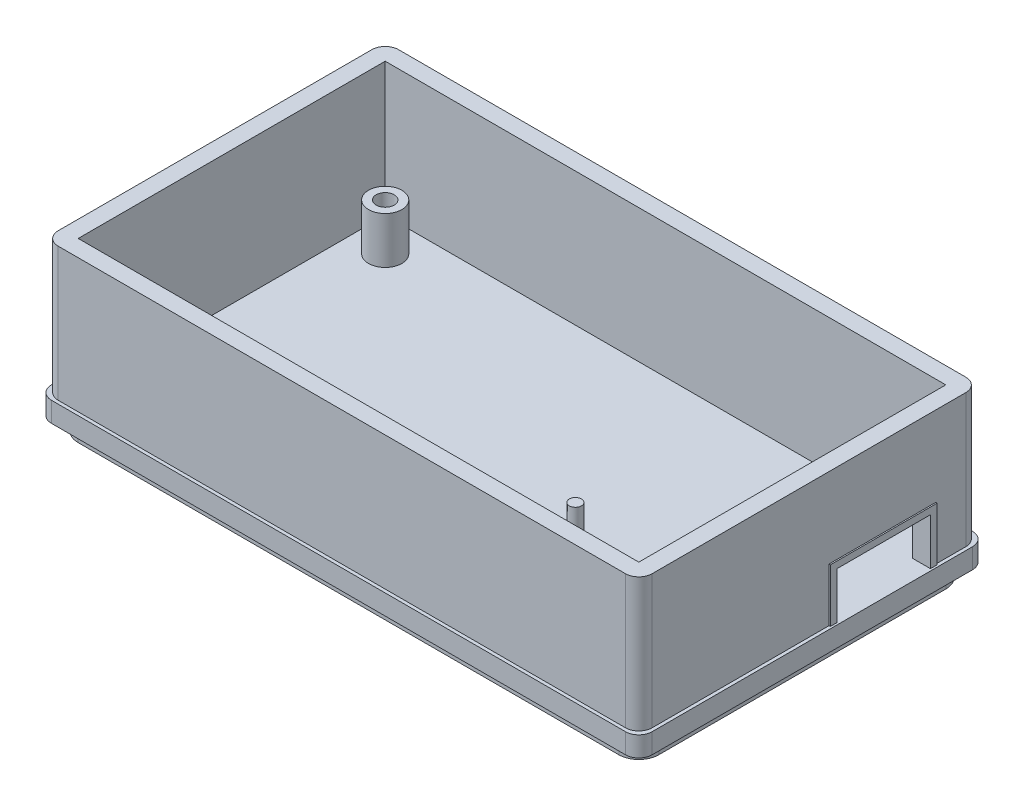
SolidWorks part; units mm, degrees
ref_plane "Front Plane" through (0, 0, 0) normal (0, 0, 1) x (1, 0, 0)
ref_plane "Top Plane" through (0, 0, 0) normal (0, 1, 0) x (1, 0, 0)
ref_plane "Right Plane" through (0, 0, 0) normal (1, 0, 0) x (0, 0, -1)
sketch "Sketch1" plane through (0, 0, 0) normal (0, 1, 0) x (1, 0, 0)
  line L1 (-45, 26) -> (45, 26)
  line L2 (-45, 26) -> (-45, -26)
  line L3 (-45, -26) -> (45, -26)
  line L4 (45, 26) -> (45, -26)
  dimension "D1" = 52
  dimension "D2" = 90
  dimension "D3" = 45
  dimension "D4" = 26
extrude "Boss-Extrude1" add sketch "Sketch1" along normal blind 3
sketch "Sketch3" plane through (0, 0, 0) normal (0, 1, 0) x (1, 0, 0)
  line L1 (-41.5, 22.5) -> (41.5, 22.5)
  line L2 (-41.5, 22.5) -> (-41.5, -22.5)
  line L3 (-41.5, -22.5) -> (41.5, -22.5)
  line L4 (41.5, 22.5) -> (41.5, -22.5)
  dimension "D1" = 45
  dimension "D2" = 83
  dimension "D3" = 41.5
  dimension "D4" = 22.5
sketch "Sketch4" plane through (0, 0, 0) normal (0, 1, 0) x (1, 0, 0)
  line L2 (-41.5, -22.5) -> (41.5, -22.5) construction
  line L3 (-41.5, 22.5) -> (-41.5, -22.5) construction
  circle A1 centre (29, -19.5) radius 2.5
  circle A2 centre (-37, 18) radius 2.5
  circle A3 centre (-37, -16.5) radius 2.5
  dimension "D4" = 5
  dimension "D5" = 3
  dimension "D8" = 4.5
  dimension "D9" = 6
extrude "Boss-Extrude2" add sketch "Sketch4" along normal blind 7 from surface at 3 starting at face at (0, 3, 0)
sketch "Sketch5" plane through (0, 0, 0) normal (0, 1, 0) x (1, 0, 0)
  circle A0 centre (-37, 18) radius 1.35
  circle A1 centre (-37, -16.5) radius 1.35
extrude "Cut-Extrude2" cut sketch "Sketch5" against normal through all both and the other way through all from surface at 10 starting at face at (-37, 10, -15.5)
sketch "Sketch6" plane through (0, 0, 0) normal (0, 1, 0) x (1, 0, 0)
  circle A0 centre (29, -19.5) radius 0.9
  dimension "D1" = 1.8
extrude "Boss-Extrude3" add sketch "Sketch6" along normal blind 12.5 from surface at 10 starting at face at (29, 10, 22)
sketch "Sketch7" plane through (0, 0, 0) normal (0, 1, 0) x (1, 0, 0)
  line L4 (40.5, 21.5) -> (-40.5, 21.5)
  line L5 (-40.5, 21.5) -> (-40.5, -21.5)
  line L6 (-40.5, -21.5) -> (40.5, -21.5)
  line L7 (40.5, -21.5) -> (40.5, 21.5)
  line L8 (43.5, 24.5) -> (-43.5, 24.5)
  line L9 (43.5, -24.5) -> (43.5, 24.5)
  line L10 (-43.5, -24.5) -> (43.5, -24.5)
  line L11 (-43.5, 24.5) -> (-43.5, -24.5)
  line L12 (43.5, 24.5) -> (-43.5, 24.5)
  line L13 (43.5, -24.5) -> (43.5, 24.5)
  line L14 (-43.5, -24.5) -> (43.5, -24.5)
  line L15 (-43.5, 24.5) -> (-43.5, -24.5)
  dimension "D1" = 2
  dimension "D2" = 3
extrude "Boss-Extrude4" add sketch "Sketch7" against normal blind 2
fillet "Fillet1" radius 3 4 edges at (-43.5, -1, 24.5) (-43.5, -1, -24.5) (43.5, -1, 24.5) (43.5, -1, -24.5)
sketch "Sketch8" plane through (0, 0, 0) normal (0, 1, 0) x (1, 0, 0)
  line L4 (44.5, 25.5) -> (-44.5, 25.5)
  line L5 (-44.5, 25.5) -> (-44.5, -25.5)
  line L6 (-44.5, -25.5) -> (44.5, -25.5)
  line L7 (44.5, -25.5) -> (44.5, 25.5)
  line L8 (42, 23) -> (-42, 23)
  line L9 (42, -23) -> (42, 23)
  line L10 (-42, -23) -> (42, -23)
  line L11 (-42, 23) -> (-42, -23)
  line L12 (42, 23) -> (-42, 23)
  line L13 (42, -23) -> (42, 23)
  line L14 (-42, -23) -> (42, -23)
  line L15 (-42, 23) -> (-42, -23)
  dimension "D1" = 0.5
  dimension "D2" = 2.5
extrude "Boss-Extrude8" add sketch "Sketch8" along normal blind 20 from surface at 3 starting at face at (29, 3, 22)
fillet "Fillet2" radius 2 8 edges at (-45, 1.5, 26) (-44.5, 13, 25.5) (-45, 1.5, -26) (-44.5, 13, -25.5) (45, 1.5, -26) (45, 1.5, 26) (44.5, 13, -25.5) (44.5, 13, 25.5)
sketch "Sketch9" plane through (0, 0, 0) normal (1, 0, 0) x (0, 0, -1)
  line L1 (4, 10) -> (18, 10)
  line L2 (4, 10) -> (4, 3)
  line L3 (4, 3) -> (18, 3)
  line L4 (18, 10) -> (18, 3)
  dimension "D1" = 14
  dimension "D2" = 7
  dimension "D4" = 5.5
extrude "Cut-Extrude3" cut sketch "Sketch9" along normal blind 15 from surface at 42 starting at face at (42, 13, 0)
sketch "Sketch10" plane through (0, 0, 0) normal (1, 0, 0) x (0, 0, -1)
  line L9 (18, 3) -> (18, 10)
  line L15 (18, 10) -> (4, 10)
  line L16 (4, 10) -> (4, 3)
  line L17 (19, 3) -> (19, 11)
  line L22 (3, 11) -> (3, 3)
  line L23 (19, 11) -> (3, 11)
  line L24 (19, 3) -> (19, 11)
  line L25 (3, 11) -> (3, 3)
  line L26 (19, 11) -> (3, 11)
  line L27 (3, 3) -> (4, 3)
  line L28 (18, 3) -> (19, 3)
  dimension "D2" = 1
  dimension "D1" = 1
extrude "Boss-Extrude9" add sketch "Sketch10" along normal blind 0.2 from surface at 44.5 starting at face at (44.5, 9.75, -5.5)
